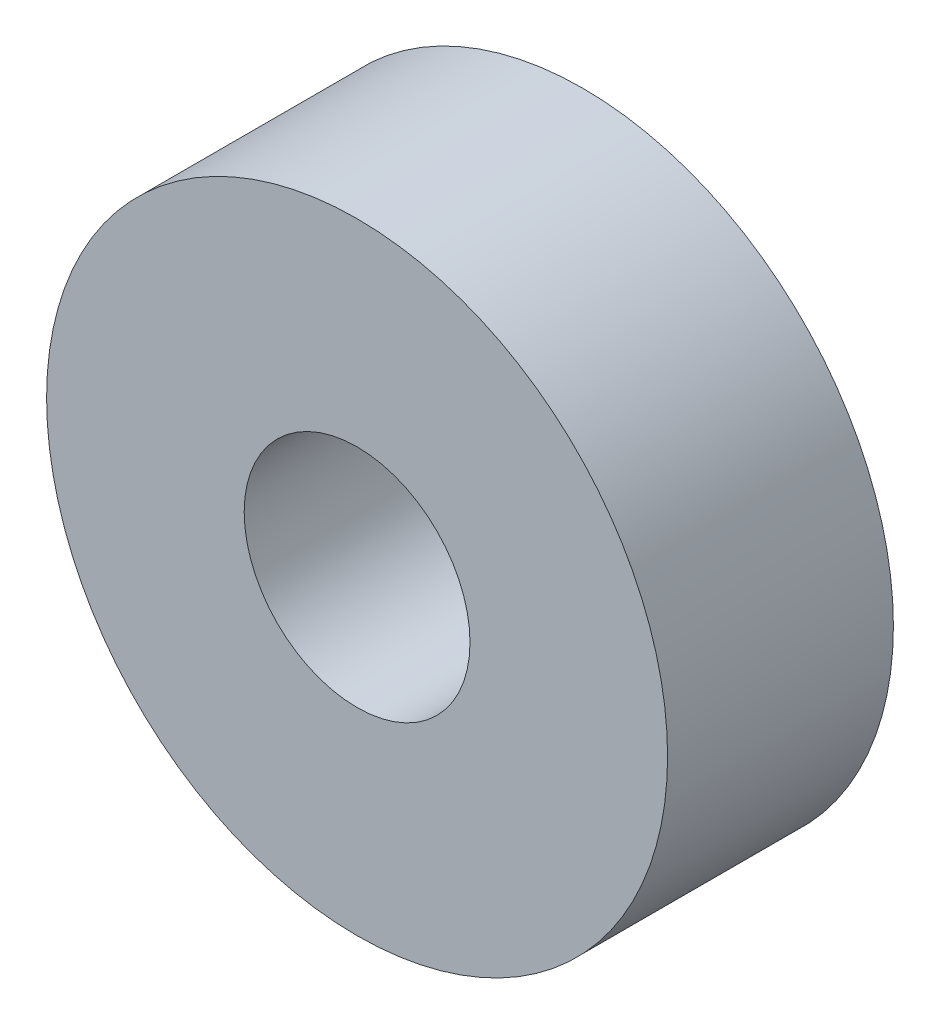
SolidWorks part; units mm, degrees
ref_plane "Спереди" through (0, 0, 0) normal (0, 0, 1) x (1, 0, 0)
ref_plane "Сверху" through (0, 0, 0) normal (0, 1, 0) x (1, 0, 0)
ref_plane "Справа" through (0, 0, 0) normal (1, 0, 0) x (0, 0, -1)
sketch "Эскиз1" plane through (0, 0, 0) normal (0, 0, 1) x (1, 0, 0)
  circle A0 centre (0, 0) radius 4
  circle A1 centre (0, 0) radius 11
extrude "Бобышка-Вытянуть1" add sketch "Эскиз1" along normal blind 8
